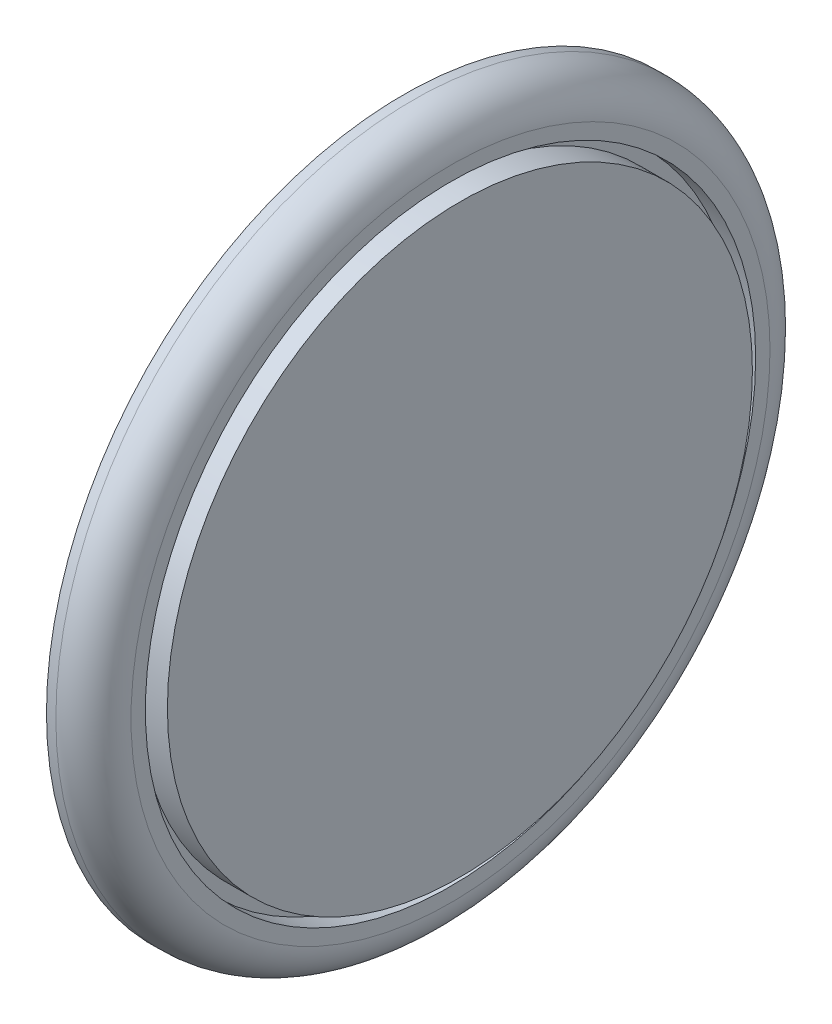
SolidWorks part; units mm, degrees
material "6061 Alloy"
ref_plane "Front Plane" through (0, 0, 0) normal (0, 0, 1) x (1, 0, 0)
ref_plane "Top Plane" through (0, 0, 0) normal (0, 1, 0) x (1, 0, 0)
ref_plane "Right Plane" through (0, 0, 0) normal (1, 0, 0) x (0, 0, -1)
sketch "Sketch1" plane through (0, 0, 0) normal (1, 0, 0) x (0, 0, -1)
  circle A0 centre (0, 0) radius 38
extrude "Boss-Extrude1" add sketch "Sketch1" along normal blind 5
fillet "Fillet1" radius 4
sketch "Sketch2" plane through (0, 0, 0) normal (-1, 0, 0) x (0, 0, 1)
  circle A0 centre (0, 0) radius 2
  circle A2 centre (0, 16.29) radius 2
  circle A3 centre (16.29, 0) radius 2
  circle A4 centre (-16.29, 0) radius 2
  circle A5 centre (0, -16.29) radius 2
extrude "Boss-Extrude2" add sketch "Sketch2" along normal blind 2.3
sketch "Sketch3" plane through (5, 0, 0) normal (1, 0, 0) x (0, 0, -1)
  circle A0 centre (0, 0) radius 32.4745
extrude "Cut-Extrude1" cut sketch "Sketch3" against normal blind 2
sketch "Sketch4" plane through (0, 0, 0) normal (-1, 0, 0) x (0, 0, 1)
  circle A0 centre (0, 0) radius 35.1917
  circle A1 centre (0, 0) radius 32.7404
extrude "Cut-Extrude2" cut sketch "Sketch4" against normal blind 2
sketch "Sketch5" plane through (3, 0, 0) normal (1, 0, 0) x (0, 0, -1)
  circle A0 centre (0, 0) radius 31.1286
extrude "Boss-Extrude3" add sketch "Sketch5" along normal blind 3
